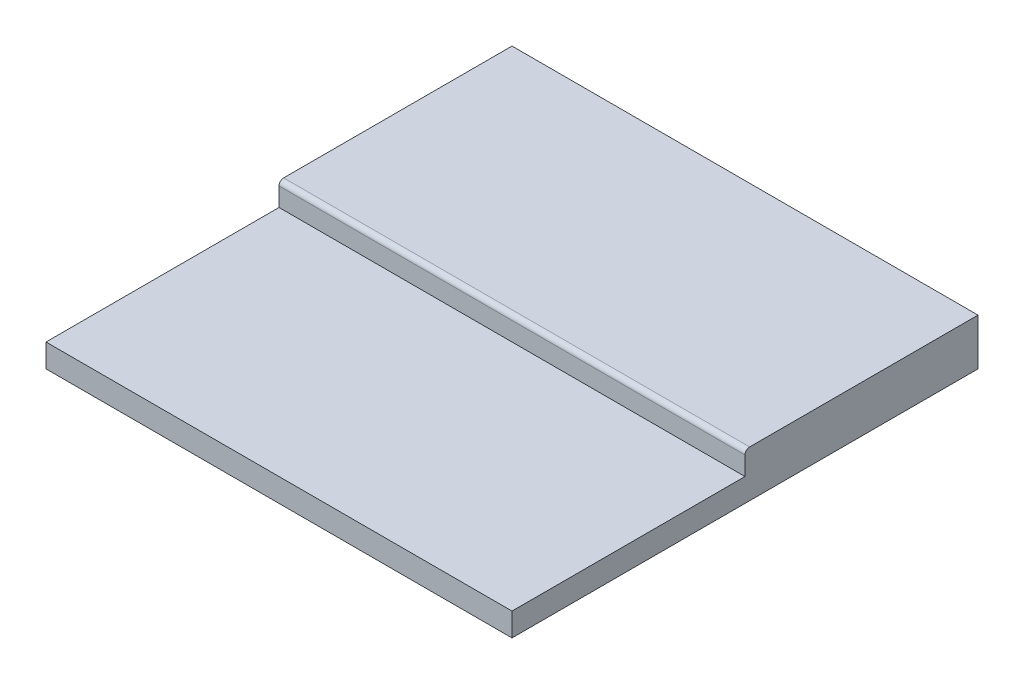
SolidWorks part; units mm, degrees
ref_plane "Front Plane" through (0, 0, 0) normal (0, 0, 1) x (1, 0, 0)
ref_plane "Top Plane" through (0, 0, 0) normal (0, 1, 0) x (1, 0, 0)
ref_plane "Right Plane" through (0, 0, 0) normal (1, 0, 0) x (0, 0, -1)
sketch "Sketch1" plane through (0, 0, 0) normal (0, 1, 0) x (1, 0, 0)
  line L1 (0, 0) -> (2000, 0)
  line L2 (0, 0) -> (0, 2000)
  line L3 (0, 2000) -> (2000, 2000)
  line L4 (2000, 0) -> (2000, 2000)
  dimension "D1" = 2000
  dimension "D2" = 2000
extrude "Boss-Extrude1" add sketch "Sketch1" along normal blind 100
sketch "Sketch2" plane through (0, 100, 0) normal (0, 1, 0) x (1, 0, 0)
  line L0 (2000, 0) -> (2000, 2000) construction
  line L1 (0, 2000) -> (2000, 2000)
  line L2 (0, 2000) -> (0, 1000)
  line L3 (0, 1000) -> (2000, 1000)
  line L4 (2000, 2000) -> (2000, 1000)
  dimension "D1" = 1000
extrude "Boss-Extrude2" add sketch "Sketch2" along normal blind 100
fillet "Fillet1" radius 20 1 edges at (1000, 200, -1000)
